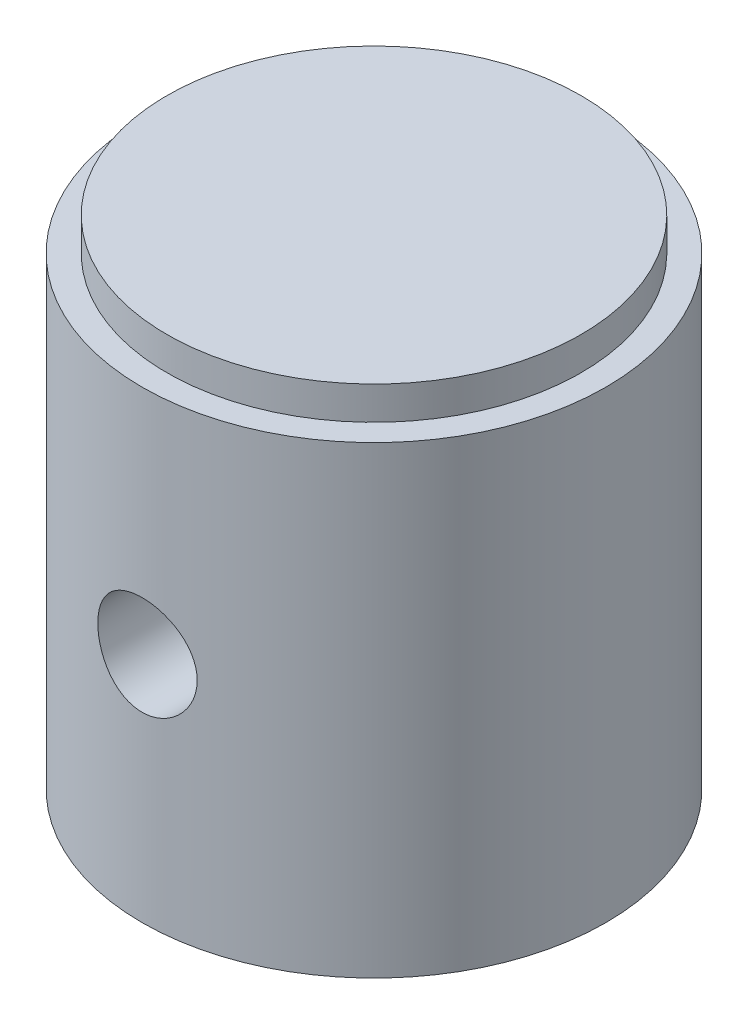
SolidWorks part; units mm, degrees
ref_plane "Ön Düzlem" through (0, 0, 0) normal (0, 0, 1) x (1, 0, 0)
ref_plane "Üst Düzlem" through (0, 0, 0) normal (0, 1, 0) x (1, 0, 0)
ref_plane "Sağ Düzlem" through (0, 0, 0) normal (1, 0, 0) x (0, 0, -1)
sketch "Sketch1" plane through (0, 0, 0) normal (0, 0, 1) x (1, 0, 0)
  line L0 (0, 2.4208) -> (0, -6.1354) construction
  line L1 (0, 9.7121) -> (-6.25, 9.7121)
  line L2 (-6.25, 9.7121) -> (-6.25, 8.7121)
  line L3 (-6.25, 8.7121) -> (-7, 8.7121)
  line L4 (-7, 8.7121) -> (-7, -5.2879)
  line L5 (-7, -5.2879) -> (-6.25, -5.2879)
  line L6 (-6.25, -5.2879) -> (-4.75, -1.1667)
  line L7 (-4.75, -1.1667) -> (-4.75, 5.7121)
  line L9 (0, 8.5662) -> (0, 9.7121)
  line L10 (-4.75, 5.7121) -> (0, 8.5662)
  line L11 (0, 2.4208) -> (0, 8.5662) construction
  dimension "D1" = 7
  dimension "D2" = 6.25
  dimension "D3" = 15
  dimension "D4" = 1
  dimension "D5" = 6.25
  dimension "D6" = 4.75
  dimension "D7" = 20
  dimension "D8" = 11
  dimension "D9" = 59
revolve "Revolve1" add sketch "Sketch1" angle 360 about L11
sketch "Sketch2" plane through (0, 0, 0) normal (0, 0, 1) x (1, 0, 0)
  line L0 (-7, -5.2879) -> (7, -5.2879) construction
  circle A0 centre (0, 1.7121) radius 1.5
  dimension "D1" = 7
extrude "Cut-Extrude1" cut sketch "Sketch2" against normal through all both and the other way through all
scale "Scale1" scale about centroid uniform scaling yes scale factor 1.5
